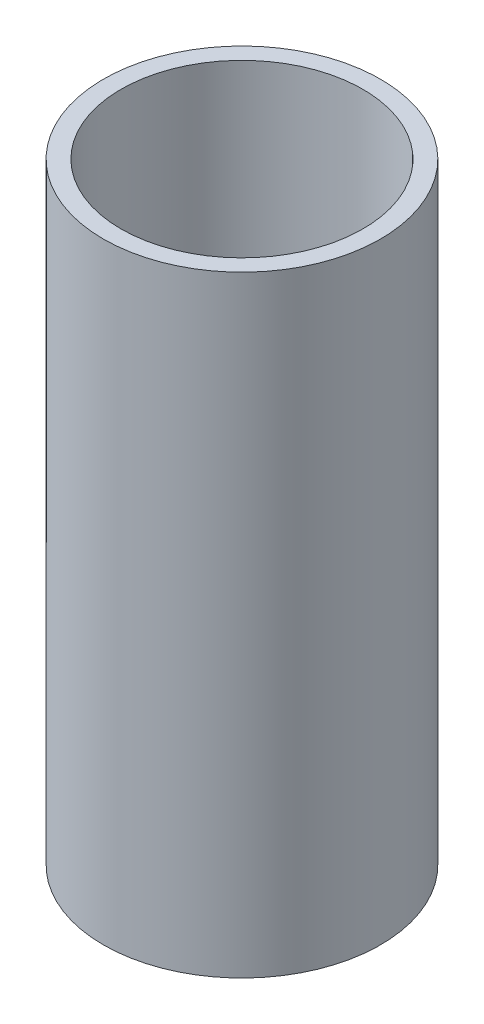
SolidWorks part; units mm, degrees
material "Rubber"
ref_plane "Front Plane" through (0, 0, 0) normal (0, 0, 1) x (1, 0, 0)
ref_plane "Top Plane" through (0, 0, 0) normal (0, 1, 0) x (1, 0, 0)
ref_plane "Right Plane" through (0, 0, 0) normal (1, 0, 0) x (0, 0, -1)
sketch "Sketch1" plane through (0, 0, 0) normal (0, 1, 0) x (1, 0, 0)
  circle A0 centre (0, 0) radius 6.135
  circle A1 centre (0, 0) radius 7.025
extrude "Boss-Extrude1" add sketch "Sketch1" along normal blind 31
